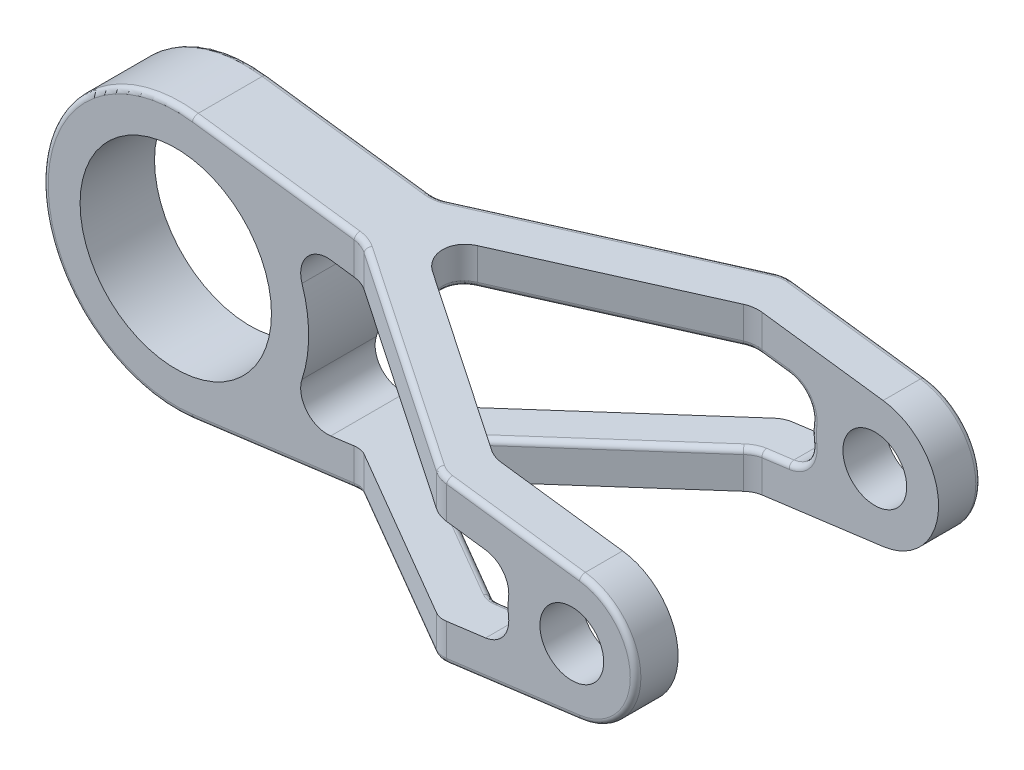
SolidWorks part; units mm, degrees
ref_plane "Front Plane" through (0, 0, 0) normal (0, 0, 1) x (1, 0, 0)
ref_plane "Top Plane" through (0, 0, 0) normal (0, 1, 0) x (1, 0, 0)
ref_plane "Right Plane" through (0, 0, 0) normal (1, 0, 0) x (0, 0, -1)
sketch "Sketch2" plane through (0, 0, 0) normal (0, 0, 1) x (1, 0, 0)
  line L0 (0, 0) -> (91.2677, 0) construction
  line L1 (3.25, 24.7878) -> (101.56, 11.8982)
  line L2 (101.56, -11.8982) -> (3.25, -24.7878)
  line L3 (29.1476, 14.3324) -> (83.7943, 7.1676)
  line L4 (29.1476, -14.3324) -> (83.7943, -7.1676)
  arc A1 (3.25, 24.7878) -> (3.25, -24.7878) centre (0, 0) ccw
  circle A2 centre (100, 0) radius 6
  arc A3 (101.56, -11.8982) -> (101.56, 11.8982) centre (100, 0) ccw
  circle A4 centre (0, 0) radius 18
  circle A5 centre (0, 0) radius 25 construction
  arc A6 (23.748, -7.8124) -> (23.748, 7.8124) centre (0, 0) ccw
  arc A7 (88.1018, 1.56) -> (88.1018, -1.56) centre (100, 0) ccw
  arc A8 (83.7943, -7.1676) -> (88.1018, -1.56) centre (83.1443, -2.21) ccw
  arc A9 (83.7943, 7.1676) -> (88.1018, 1.56) centre (83.1443, 2.21) cw
  arc A10 (29.1476, -14.3324) -> (23.748, -7.8124) centre (28.4976, -9.3749) cw
  arc A11 (29.1476, 14.3324) -> (23.748, 7.8124) centre (28.4976, 9.3749) ccw
  point P24 (89.8339, 6.3757)
  point P27 (19.5421, -15.5918)
  dimension "D1" = 50
  dimension "D3" = 24
  dimension "D4" = 12
  dimension "D7" = 5
  dimension "D5" = 100
  dimension "D6" = 7
  dimension "D2" = 7
extrude "Boss-Extrude1" add sketch "Sketch2" along normal mid plane 65
sketch "Sketch3" plane through (0, 0, 0) normal (0, 1, 0) x (1, 0, 0)
  line L0 (-34.0495, 0) -> (121.9297, 0) construction
  line L1 (-25, 7) -> (33.5418, 7)
  line L2 (-25, 32.5) -> (-25, -32.5) construction
  line L3 (36.2296, 7.7839) -> (73.7704, 31.7161)
  line L4 (76.4582, 32.5) -> (112, 32.5)
  line L5 (106, 32.5) -> (94, 32.5) construction
  line L6 (76.1035, -23.7161) -> (45.5153, -4.2161)
  line L7 (112, -24.5) -> (78.7913, -24.5)
  line L8 (112, -32.5) -> (112, -24.5)
  line L9 (112, 32.5) -> (101.56, 32.5) construction
  line L10 (112, -32.5) -> (112, 32.5) construction
  line L11 (112, 32.5) -> (112, 24.5)
  line L12 (112, 24.5) -> (78.7913, 24.5)
  line L13 (76.1035, 23.7161) -> (45.5153, 4.2161)
  line L14 (76.4582, -32.5) -> (112, -32.5)
  line L15 (36.2296, -7.7839) -> (73.7704, -31.7161)
  line L16 (-25, -7) -> (33.5418, -7)
  line L17 (-25, 7) -> (-25, -7)
  arc A0 (36.2296, -7.7839) -> (33.5418, -7) centre (33.5418, -12) ccw
  arc A1 (33.5418, 7) -> (36.2296, 7.7839) centre (33.5418, 12) ccw
  arc A2 (76.4582, -32.5) -> (73.7704, -31.7161) centre (76.4582, -27.5) cw
  arc A3 (73.7704, 31.7161) -> (76.4582, 32.5) centre (76.4582, 27.5) cw
  arc A4 (76.1035, -23.7161) -> (78.7913, -24.5) centre (78.7913, -19.5) ccw
  arc A5 (45.5153, 4.2161) -> (45.5153, -4.2161) centre (48.2031, 0) ccw
  arc A6 (78.7913, 24.5) -> (76.1035, 23.7161) centre (78.7913, 19.5) ccw
  point P26 (35, -7)
  point P29 (35, 7)
  point P32 (75, -32.5)
  point P35 (75, 32.5)
  point P38 (77.3331, -24.5)
  point P41 (38.9017, 0)
  point P44 (77.3331, 24.5)
  dimension "D6" = 5
  dimension "D1" = 7
  dimension "D2" = 60
  dimension "D3" = 100
  dimension "D4" = 8
  dimension "D5" = 8
extrude "Cut-Extrude2" cut sketch "Sketch3" against normal mid plane 80 flip side to cut
fillet "Fillet1" radius 1 44 edges at (-25, 0, -7) (18.3959, -22.802, -7) (34.9417, -20.6327, -7.2) (55, -18.0028, -19.75) (75.0583, -15.3729, -32.3) (89.0091, -13.5437, -32.5) (112, 0, -32.5) (89.0091, 13.5437, -32.5) (75.0583, 15.3729, -32.3) (55, 18.0028, -19.75) (34.9417, 20.6327, -7.2) (43.2031, -12.4896, 0) (60.8094, -10.1812, 13.9661) (77.3914, -8.0071, 24.3) (81.2928, -7.4955, 24.5) (87.1094, -5.2559, 24.5) (88, 0, 24.5) (87.1094, 5.2559, 24.5) (81.2928, 7.4955, 24.5) (77.3914, 8.0071, 24.3) (60.8094, 10.1812, 13.9661) (43.2031, 12.4896, 0) (60.8094, 10.1812, -13.9661) (77.3914, 8.0071, -24.3) (81.2928, 7.4955, -24.5) (87.1094, 5.2559, -24.5) (88, 0, -24.5) (87.1094, -5.2559, -24.5) (81.2928, -7.4955, -24.5) (77.3914, -8.0071, -24.3) (34.9417, 20.6327, 7.2) (55, 18.0028, 19.75) (75.0583, 15.3729, 32.3) (89.0091, 13.5437, 32.5) (112, 0, 32.5) (89.0091, -13.5437, 32.5) (75.0583, -15.3729, 32.3) (55, -18.0028, 19.75) (34.9417, -20.6327, 7.2) (18.3959, -22.802, 7) (-25, 0, 7) (18.3959, 22.802, -7) (60.8094, -10.1812, -13.9661) (18.3959, 22.802, 7)
